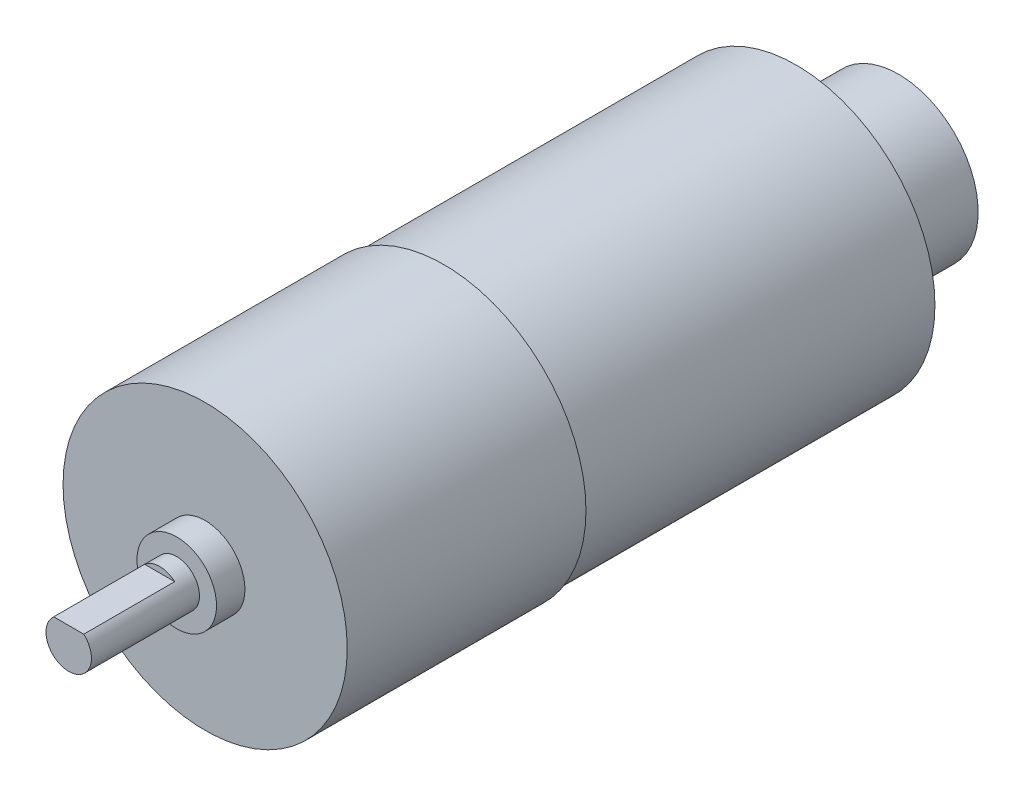
SolidWorks part; units mm, degrees
ref_plane "Front Plane" through (0, 0, 0) normal (0, 0, 1) x (1, 0, 0)
ref_plane "Top Plane" through (0, 0, 0) normal (0, 1, 0) x (1, 0, 0)
ref_plane "Right Plane" through (0, 0, 0) normal (1, 0, 0) x (0, 0, -1)
sketch "Sketch1" plane through (0, 0, 0) normal (0, 0, 1) x (1, 0, 0)
  circle A0 centre (0, 0) radius 12.2
  dimension "D1" = 24.4
extrude "Boss-Extrude1" add sketch "Sketch1" along normal blind 31
sketch "Sketch2" plane through (0, 0, 31) normal (0, 0, 1) x (1, 0, 0)
  circle A0 centre (0, 0) radius 12.5
  dimension "D1" = 25
extrude "Boss-Extrude2" add sketch "Sketch2" along normal blind 21
sketch "Sketch3" plane through (0, 0, 52) normal (0, 0, 1) x (1, 0, 0)
  circle A0 centre (0, 0) radius 3.5
  dimension "D1" = 7
extrude "Boss-Extrude3" add sketch "Sketch3" along normal blind 2.5
sketch "Sketch4" plane through (0, 0, 54.5) normal (0, 0, 1) x (1, 0, 0)
  circle A0 centre (0, 0) radius 2
  dimension "D1" = 4
extrude "Boss-Extrude5" add sketch "Sketch4" along normal blind 1.5 contours A0
sketch "Sketch5" plane through (0, 0, 56) normal (0, 0, 1) x (1, 0, 0)
  line L0 (0, 1.5) -> (1.3229, 1.5)
  line L2 (0, 1.5) -> (-1.3229, 1.5)
  circle A0 centre (0, 0) radius 2 construction
  circle A1 centre (0, 0) radius 2 construction
  arc A2 (-1.3229, 1.5) -> (1.3229, 1.5) centre (0, 0) ccw
  dimension "D1" = 1.5
extrude "Boss-Extrude6" add sketch "Sketch5" along normal blind 8
sketch "Sketch6" plane through (0, 0, 0) normal (0, 0, -1) x (-1, 0, 0)
  circle A0 centre (0, 0) radius 0.5
  dimension "D1" = 1
extrude "Boss-Extrude7" add sketch "Sketch6" along normal blind 1
sketch "Sketch7" plane through (0, 0, -1) normal (0, 0, -1) x (-1, 0, 0)
  circle A0 centre (0, 0) radius 7
  dimension "D1" = 14
extrude "Boss-Extrude8" add sketch "Sketch7" along normal blind 8
